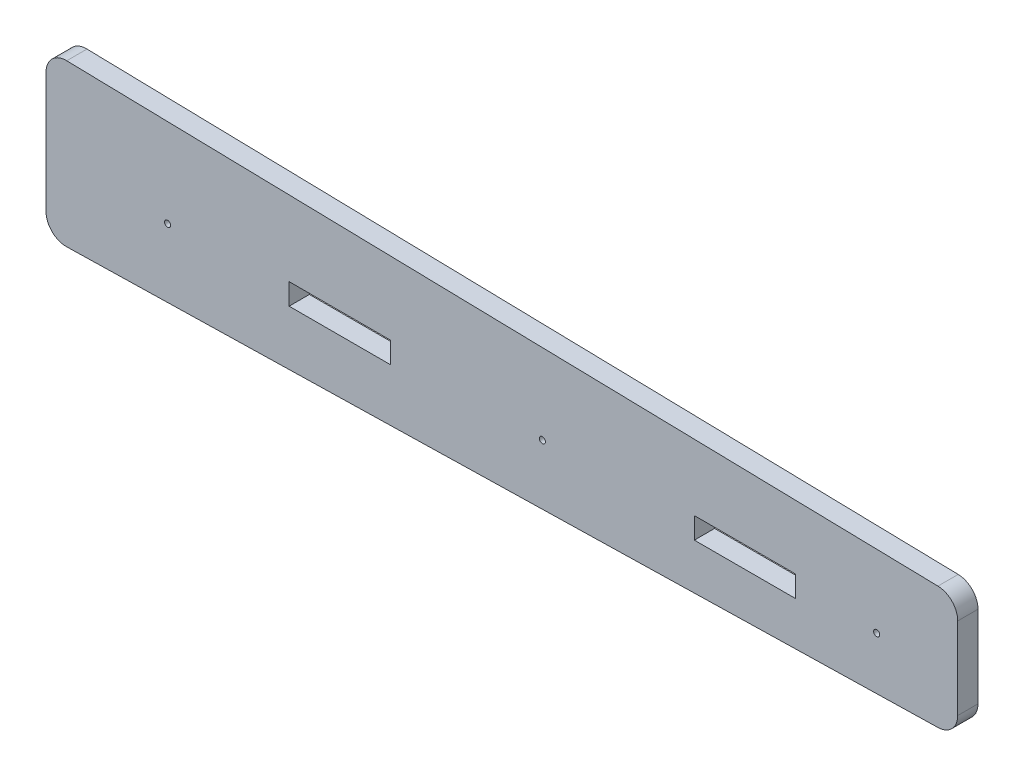
SolidWorks part; units mm, degrees
material "Teak"
ref_plane "Front Plane" through (0, 0, 0) normal (0, 0, 1) x (1, 0, 0)
ref_plane "Top Plane" through (0, 0, 0) normal (0, 1, 0) x (1, 0, 0)
ref_plane "Right Plane" through (0, 0, 0) normal (1, 0, 0) x (0, 0, -1)
sketch "Sketch1" plane through (0, 0, 0) normal (0, 0, 1) x (1, 0, 0)
  line L0 (-225, 40) -> (-225, -40)
  line L5 (-225, -40) -> (225, -30)
  line L6 (225, -30) -> (225, 30)
  line L7 (-105, 0.25) -> (-55, 0.25)
  line L8 (-105, 0.25) -> (-105, -10.25)
  line L9 (-105, -10.25) -> (-55, -10.25)
  line L10 (-55, 0.25) -> (-55, -10.25)
  line L11 (-105, 0.25) -> (-55, -10.25) construction
  line L12 (-105, -10.25) -> (-55, 0.25) construction
  line L13 (95, 0.25) -> (145, 0.25)
  line L14 (95, 0.25) -> (95, -10.25)
  line L15 (95, -10.25) -> (145, -10.25)
  line L16 (145, 0.25) -> (145, -10.25)
  line L17 (95, 0.25) -> (145, -10.25) construction
  line L18 (95, -10.25) -> (145, 0.25) construction
  line L19 (225, 30) -> (-225, 40)
  point P0 (0, 0)
  point P4 (-225, 0)
  point P11 (120, -5)
  point P17 (225, 0)
  point P22 (0, 35)
  point P26 (-80, -5)
  dimension "D1" = 50
  dimension "D2" = 10.5
  dimension "D3" = 60
  dimension "D4" = 80
  dimension "D5" = 450
  dimension "D6" = 150
  dimension "D7" = 80
  dimension "D8" = 5
extrude "Основа" add sketch "Sketch1" along normal blind 10
fillet "Fillet1" radius 10 4 edges at (-225, -40, 5) (-225, 40, 5) (225, -30, 5) (225, 30, 5)
sketch "Sketch2" plane through (0, 0, 10) normal (0, 0, 1) x (1, 0, 0)
  line L0 (-55, -10.25) -> (-55, 0.25) construction
  line L1 (145, -5) -> (225, -5) construction
  line L2 (145, -10.25) -> (145, 0.25) construction
  line L3 (225, -20.2198) -> (225, 20.2198) construction
  line L4 (95, -5) -> (-55, -5) construction
  line L5 (95, 0.25) -> (95, -10.25) construction
  line L6 (-105, -5) -> (-225, -5) construction
  line L7 (-105, 0.25) -> (-105, -10.25) construction
  line L8 (-225, 29.7753) -> (-225, -29.7753) construction
  circle A0 centre (-165, -5) radius 1.5
  circle A1 centre (20, -5) radius 1.5
  circle A2 centre (185, -5) radius 1.5
  point P9 (-55, -5)
  point P25 (185, -5)
  point P26 (20, -5)
  point P28 (-165, -5)
  dimension "D1" = 3
extrude "Под шурупы" cut sketch "Sketch2" against normal up to next
